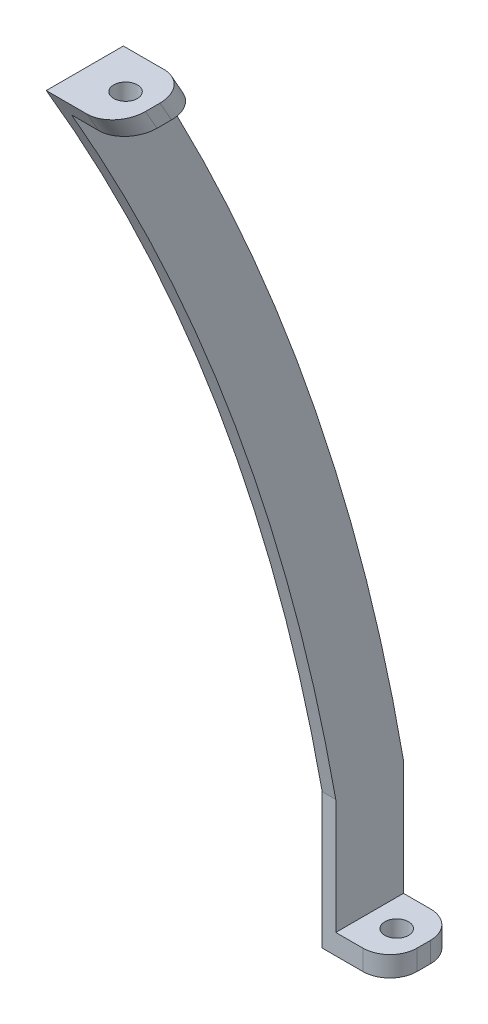
SolidWorks part; units mm, degrees
ref_plane "Front Plane" through (0, 0, 0) normal (0, 0, 1) x (1, 0, 0)
ref_plane "Top Plane" through (0, 0, 0) normal (0, 1, 0) x (1, 0, 0)
ref_plane "Right Plane" through (0, 0, 0) normal (1, 0, 0) x (0, 0, -1)
sketch "Sketch1" plane through (0, 0, 0) normal (1, 0, 0) x (0, 0, -1)
  line L0 (-40.7368, 130) -> (-29.3536, 130)
  line L1 (0, 0) -> (10, 0)
  line L2 (0, 0) -> (0, 20)
  line L4 (10, 0) -> (10, 20)
  arc A0 (0, 20) -> (-40.7368, 130) centre (-324.5568, -37.6516) ccw
  arc A1 (10, 20) -> (-29.3536, 130) centre (-324.5568, -37.6516) ccw
  dimension "D1" = 10
  dimension "D2" = 20
  dimension "D3" = 130
extrude "Boss-Extrude1" add sketch "Sketch1" along normal blind 2
sketch "Sketch2" plane through (2, 0, 0) normal (1, 0, 0) x (0, 0, -1)
  line L0 (10, 0) -> (10, 20) construction
  line L1 (0, 0) -> (10, 0)
  line L2 (0, 0) -> (0, 3)
  line L3 (0, 3) -> (10, 3)
  line L4 (10, 0) -> (10, 3)
  line L5 (-40.7368, 130) -> (-29.3536, 130)
  line L6 (-38.986, 127) -> (-27.6699, 127)
  arc A0 (0, 20) -> (-40.7368, 130) centre (-324.5568, -37.6516) ccw construction
  arc A1 (10, 20) -> (-29.3536, 130) centre (-324.5568, -37.6516) ccw construction
  arc A2 (-40.7368, 130) -> (-38.986, 127) centre (-324.5568, -37.6516) cw
  arc A3 (-29.3536, 130) -> (-27.6699, 127) centre (-324.5568, -37.6516) cw
  dimension "D1" = 3
  dimension "D2" = 3
extrude "Boss-Extrude2" add sketch "Sketch2" along normal blind 8
fillet "Fillet1" radius 4 4 edges at (10, 1.5, -10) (10, 1.5, 0) (10, 128.5021, 28.508) (10, 128.5023, 39.8575)
sketch "Sketch3" plane through (0, 3, 0) normal (0, 1, 0) x (1, 0, 0)
  line L0 (10, 5) -> (6, 5) construction
  line L1 (10, 6) -> (10, 4) construction
  line L2 (10, -35.0317) -> (6, -35.0317) construction
  line L3 (10, -33.9626) -> (10, -36.1008) construction
  circle A0 centre (6, 5) radius 1.75
  circle A1 centre (6, -35.0317) radius 1.75
  dimension "D2" = 3.5
  dimension "D4" = 3.5
  dimension "D1" = 4
  dimension "D3" = 4
extrude "Cut-Extrude1" cut sketch "Sketch3" against normal through all both and the other way through all
